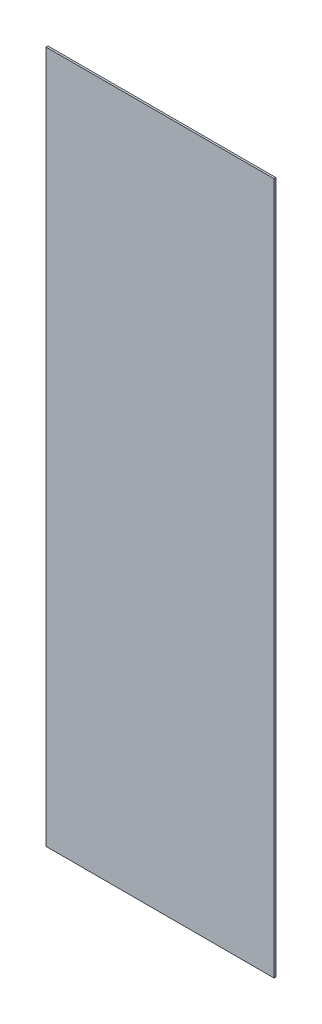
SolidWorks part; units mm, degrees
ref_plane "前视基准面" through (0, 0, 0) normal (0, 0, 1) x (1, 0, 0)
ref_plane "上视基准面" through (0, 0, 0) normal (0, 1, 0) x (1, 0, 0)
ref_plane "右视基准面" through (0, 0, 0) normal (1, 0, 0) x (0, 0, -1)
sketch "草图1" plane through (0, 0, 0) normal (0, 0, 1) x (1, 0, 0)
  line L1 (156.5, -10) -> (275, -10)
  line L2 (156.5, -10) -> (156.5, -370)
  line L3 (156.5, -370) -> (275, -370)
  line L4 (275, -10) -> (275, -370)
extrude "凸台-拉伸1" add sketch "草图1" against normal blind 1
